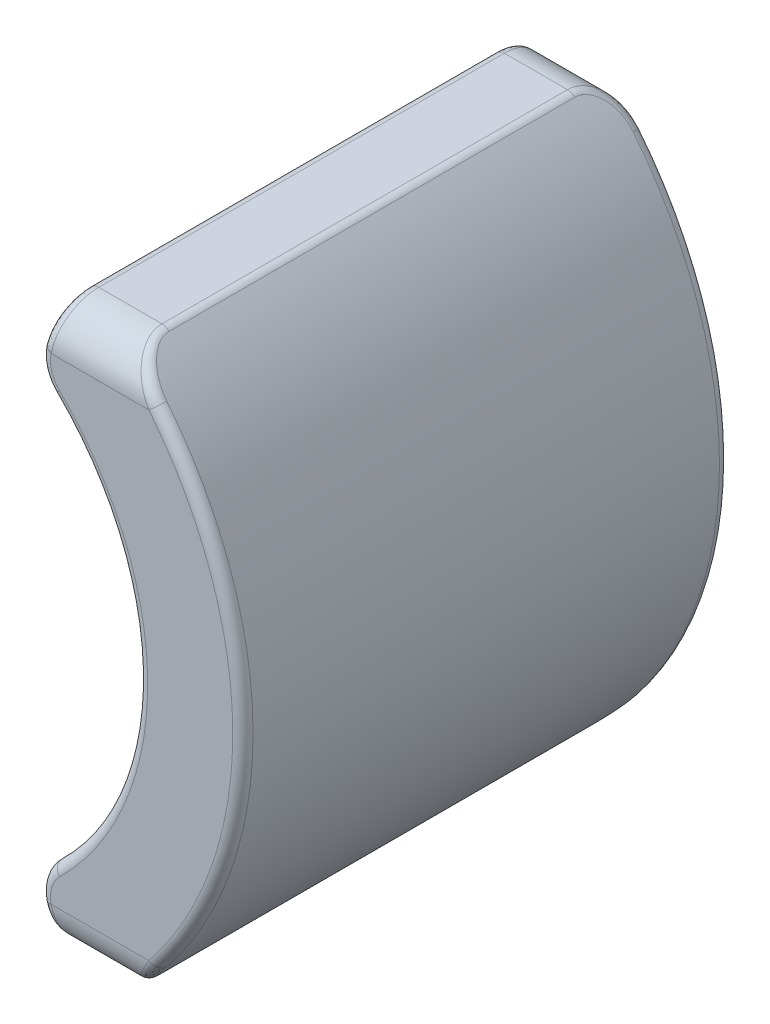
SolidWorks part; units mm, degrees
ref_plane "Front Plane" through (0, 0, 0) normal (0, 0, 1) x (1, 0, 0)
ref_plane "Top Plane" through (0, 0, 0) normal (0, 1, 0) x (1, 0, 0)
ref_plane "Right Plane" through (0, 0, 0) normal (1, 0, 0) x (0, 0, -1)
sketch "Sketch1" plane through (0, 0, 0) normal (0, 0, 1) x (1, 0, 0)
  line L0 (0, 0) -> (9.63, 0) construction
  line L1 (6.7381, -6.88) -> (4.8781, -6.88)
  line L2 (4.8781, -6.88) -> (4.5318, -5.38)
  line L3 (6.7381, 6.88) -> (4.8781, 6.88)
  line L4 (4.8781, 6.88) -> (4.5318, 5.38)
  arc A0 (6.7381, 6.88) -> (6.7381, -6.88) centre (0, 0) cw
  arc A1 (4.5318, 5.38) -> (4.5318, -5.38) centre (0, 0) cw
  dimension "D2" = 6.88
  dimension "D1" = 9.63
  dimension "D3" = 1.86
  dimension "D4" = 1.5
  dimension "D5" = 103
extrude "Boss-Extrude1" add sketch "Sketch1" along normal blind 12
fillet "Fillet1" radius 1 2 edges at (4.5318, -5.38, 6) (4.5318, 5.38, 6)
fillet "Fillet2" radius 1 4 edges at (5.8081, -6.88, 0) (5.8081, -6.88, 12) (5.8081, 6.88, 0) (5.8081, 6.88, 12)
fillet "Fillet3" radius 0.25 24 edges at (4.8161, 6.6112, 11.6822) (4.6879, 5.4113, 12) (7.0343, 0, 12) (4.6879, -5.4113, 12) (4.8161, -6.6112, 11.6822) (4.8781, -6.88, 6) (4.8161, -6.6112, 0.3178) (4.6879, -5.4113, 0) (7.0343, 0, 0) (4.6879, 5.4113, 0) (4.8161, 6.6112, 0.3178) (6.8685, 6.7498, 11.4934) (9.63, 0, 12) (6.9882, -6.6258, 11.6661) (6.7381, -6.88, 6) (6.8685, -6.7498, 0.5066) (9.63, 0, 0) (6.9882, 6.6258, 0.3339) (4.8781, 6.88, 6) (6.7381, 6.88, 6)
scale "Scale1" scale about origin uniform scaling yes scale factor 0.445
